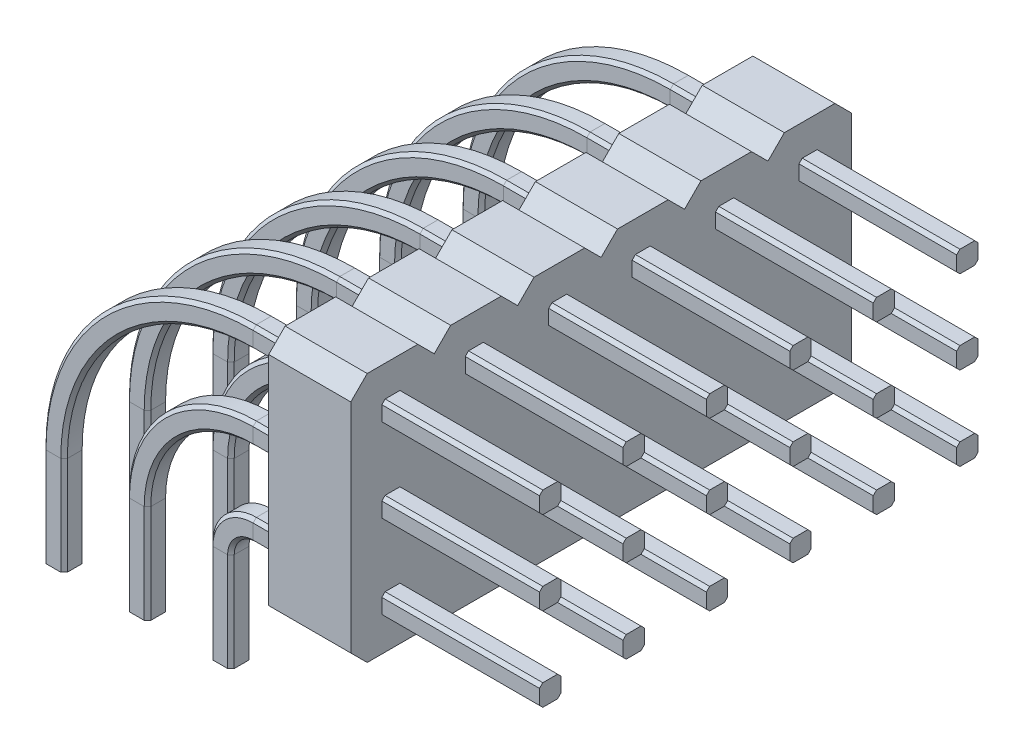
SolidWorks part; units mm, degrees
ref_plane "Front Plane" through (0, 0, 0) normal (0, 0, 1) x (1, 0, 0)
ref_plane "Top Plane" through (0, 0, 0) normal (0, 1, 0) x (1, 0, 0)
ref_plane "Right Plane" through (0, 0, 0) normal (1, 0, 0) x (0, 0, -1)
sketch "Sketch1" plane through (0, 0, 0) normal (0, 1, 0) x (1, 0, 0)
  line L0 (-0.325, 0.225) -> (-0.225, 0.325)
  line L1 (-0.225, -0.325) -> (0.225, -0.325)
  line L2 (-0.325, -0.225) -> (-0.325, 0.225)
  line L3 (-0.225, 0.325) -> (0.225, 0.325)
  line L4 (0.325, -0.225) -> (0.325, 0.225)
  line L5 (-0.325, -0.325) -> (0.325, 0.325) construction
  line L6 (-0.325, 0.325) -> (0.325, -0.325) construction
  line L7 (-0.225, -0.325) -> (-0.325, -0.225)
  line L8 (0.225, -0.325) -> (0.325, -0.225)
  line L9 (0.225, 0.325) -> (0.325, 0.225)
  line L10 (2.215, 0.225) -> (2.315, 0.325)
  line L11 (2.315, -0.325) -> (2.765, -0.325)
  line L12 (2.215, -0.225) -> (2.215, 0.225)
  line L13 (2.315, 0.325) -> (2.765, 0.325)
  line L14 (2.865, -0.225) -> (2.865, 0.225)
  line L15 (2.315, -0.325) -> (2.215, -0.225)
  line L16 (2.765, -0.325) -> (2.865, -0.225)
  line L17 (2.765, 0.325) -> (2.865, 0.225)
  line L18 (2.215, -0.325) -> (2.865, 0.325) construction
  line L19 (2.215, 0.325) -> (2.865, -0.325) construction
  line L20 (4.755, 0.225) -> (4.855, 0.325)
  line L21 (4.855, -0.325) -> (5.305, -0.325)
  line L22 (4.755, -0.225) -> (4.755, 0.225)
  line L23 (4.855, 0.325) -> (5.305, 0.325)
  line L24 (5.405, -0.225) -> (5.405, 0.225)
  line L25 (4.855, -0.325) -> (4.755, -0.225)
  line L26 (5.305, -0.325) -> (5.405, -0.225)
  line L27 (5.305, 0.325) -> (5.405, 0.225)
  line L28 (4.755, -0.325) -> (5.405, 0.325) construction
  line L29 (4.755, 0.325) -> (5.405, -0.325) construction
  line L30 (0, 0) -> (5.08, 0) construction
  point P0 (0, 0)
  point P16 (2.54, 0)
  point P29 (5.08, 0)
  dimension "D1" = 0.65
  dimension "D2" = 3
  dimension "D3" = 2.54
sketch "Sketch2" plane through (0, 0, 0) normal (0, 0, 1) x (1, 0, 0)
  line L0 (5.08, 0) -> (5.08, 3)
  line L1 (6.08, 4) -> (14.8, 4)
  line L2 (2.54, 0) -> (2.54, 5.54)
  line L3 (3.54, 6.54) -> (14.8, 6.54)
  line L4 (0, 0) -> (0, 8.08)
  line L5 (-0.225, 0) -> (0.225, 0) construction
  line L6 (1, 9.08) -> (14.8, 9.08)
  arc A0 (0, 8.08) -> (1, 9.08) centre (1, 8.08) cw
  arc A1 (2.54, 5.54) -> (3.54, 6.54) centre (3.54, 5.54) cw
  arc A2 (5.08, 3) -> (6.08, 4) centre (6.08, 3) cw
  point P16 (0, 9.08)
  point P19 (2.54, 6.54)
  point P22 (5.08, 4)
  dimension "D5" = 1
  dimension "D1" = 4
  dimension "D2" = 6.54
  dimension "D3" = 9.08
  dimension "D4" = 9.72
sweep "Sweep2" add profiles "Sketch1" path "Sketch2"
ref_plane "Plane1" through (7.5, 0, 0) normal (1, 0, 0) x (0, 0, -1)
sketch "Sketch4" plane through (7.5, 0, 0) normal (1, 0, 0) x (0, 0, -1)
  line L1 (-0.77, 10.35) -> (0.77, 10.35)
  line L2 (-1.27, 9.85) -> (-1.27, 3.23)
  line L3 (-0.77, 2.73) -> (0.77, 2.73)
  line L4 (1.27, 9.85) -> (1.27, 3.23)
  line L5 (-1.27, 10.35) -> (1.27, 2.73) construction
  line L6 (-1.27, 2.73) -> (1.27, 10.35) construction
  line L7 (-0.225, 6.215) -> (0.225, 6.215) construction
  line L10 (0.325, 6.315) -> (0.325, 6.765) construction
  line L11 (0.77, 10.35) -> (1.27, 9.85)
  line L12 (-1.27, 9.85) -> (-0.77, 10.35)
  line L13 (0.77, 2.73) -> (1.27, 3.23)
  line L14 (-1.27, 3.23) -> (-0.77, 2.73)
  point P0 (0, 6.54)
  point P5 (0, 0)
  point P10 (0.325, 6.54)
  point P13 (0, 0)
  point P14 (0, 6.215)
  dimension "D1" = 2.54
  dimension "D2" = 7.62
extrude "Boss-Extrude1" add sketch "Sketch4" along normal blind 2.5
pattern_linear "LPattern1" count 6 spacing 2.54 along (0, 0, 1) of bodies 107
combine bodies "Combine1" operation type add bodies to combine 109 112 110 108 111 107
